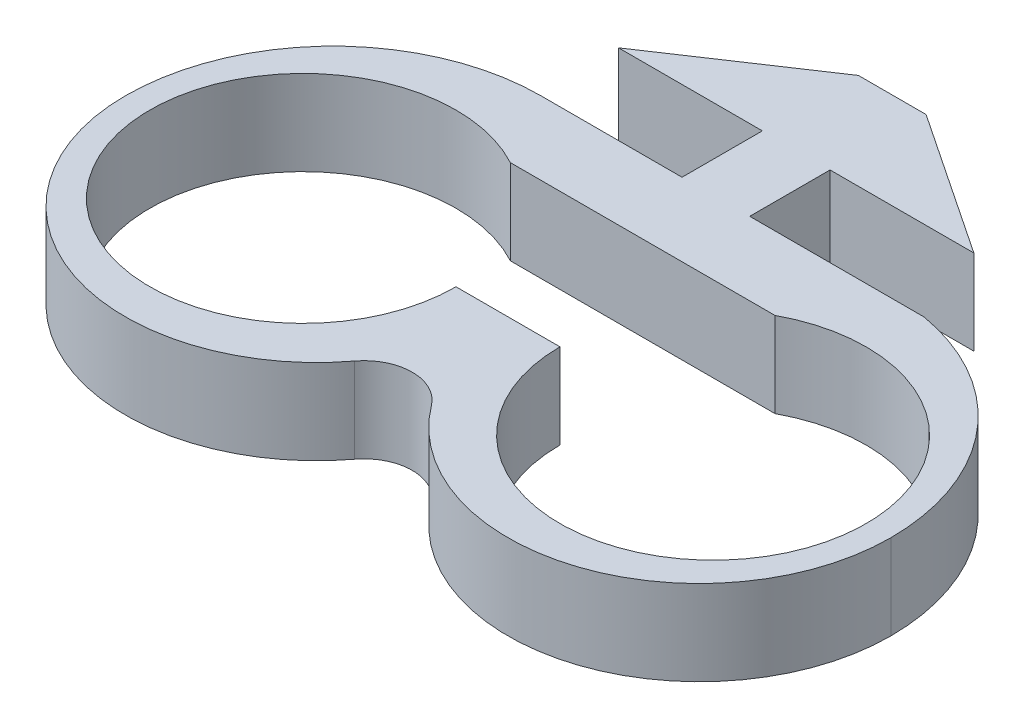
SolidWorks part; units mm, degrees
ref_plane "Front" through (0, 0, 0) normal (0, 0, 1) x (1, 0, 0)
ref_plane "Top" through (0, 0, 0) normal (0, 1, 0) x (1, 0, 0)
ref_plane "Right" through (0, 0, 0) normal (1, 0, 0) x (0, 0, -1)
sketch "Sketch1" plane through (0, 0, 0) normal (0, 1, 0) x (1, 0, 0)
  line L0 (-1.7907, 2.125) -> (-9.398, 2.125)
  line L2 (-1.7907, -2.125) -> (-1.7907, 2.125)
  line L4 (1.7907, -2.125) -> (1.7907, 2.125)
  line L7 (-9.398, 2.125) -> (-1.7907, 7.205)
  line L8 (-1.7907, 7.205) -> (1.7907, 7.205)
  line L9 (1.7907, 7.205) -> (9.398, 2.125)
  line L10 (9.398, 2.125) -> (1.7907, 2.125)
  line L11 (1.7907, -2.125) -> (20.25, -2.125)
  line L12 (-1.7907, -2.125) -> (-20.25, -2.125)
  line L13 (-20.25, -2.125) -> (-20.25, -13.1232)
  line L14 (-20.25, -13.1232) -> (20.25, -13.1232)
  line L15 (20.25, -13.1232) -> (20.25, -2.125)
  line L16 (20.25, -2.125) -> (1.7907, -2.125)
  point P0 (0, 0)
  point P17 (0, 7.205)
  point P19 (0, -13.1232)
  point P24 (1.7907, 0)
  dimension "D1" = 18.796
  dimension "D2" = 3.5814
  dimension "D3" = 40.5
  dimension "D4" = 10.9982
  dimension "D5" = 5.08
  dimension "4.2" = 4.25
extrude "Boss-Extrude1" add sketch "Sketch1" along normal blind 4.5 contours L14 L15 L11 L4 L10 L9 L8 L7 L0 L2 L12 L13
sketch "Sketch3" plane through (0, 4.5, 0) normal (0, 1, 0) x (1, 0, 0)
  line L3 (-20.25, -13.1232) -> (20.25, -13.1232) construction
  line L16 (-20.25, -13.1232) -> (20.25, -13.1232)
  line L17 (20.25, -13.1232) -> (20.25, -2.125)
  line L18 (20.25, -2.125) -> (1.7907, -2.125)
  line L19 (1.7907, -2.125) -> (1.7907, 2.125)
  line L20 (1.7907, 2.125) -> (9.398, 2.125)
  line L21 (9.398, 2.125) -> (1.7907, 7.205)
  line L22 (1.7907, 7.205) -> (-1.7907, 7.205)
  line L23 (-1.7907, 7.205) -> (-9.398, 2.125)
  line L24 (-9.398, 2.125) -> (-1.7907, 2.125)
  line L25 (-1.7907, 2.125) -> (-1.7907, -2.125)
  line L26 (-1.7907, -2.125) -> (-20.25, -2.125)
  line L27 (-20.25, -2.125) -> (-20.25, -13.1232)
  line L28 (-20.25, -13.1232) -> (20.25, -13.1232)
  arc A2 (-20.25, -13.1232) -> (-2.0306, -19.2057) centre (-10.125, -13.1232) ccw
  arc A3 (2.0306, -19.2057) -> (20.25, -13.1232) centre (10.125, -13.1232) ccw
  arc A4 (2.0306, -19.2057) -> (-2.0306, -19.2057) centre (0, -20.7315) ccw
  point P14 (0, -13.1232)
  line M15 (-20.25, -13.1232) -> (20.25, -13.1232)
  dimension "D2" = 2.54
  dimension "D1" = 0
extrude "Boss-Extrude2" add sketch "Sketch3" against normal up to surface (4.5 mm away) contours A2 M15 | L28 A3 up to face at (0, 0, 0.9864)
sketch "Sketch4" plane through (0, 4.5, 0) normal (0, 1, 0) x (1, 0, 0)
  line L1 (2.75, -13.1232) -> (-2.75, -13.1232) construction
  circle A0 centre (-10.85, -13.1232) radius 8.1
  circle A1 centre (10.85, -13.1232) radius 8.1
  point P4 (0, -13.1232)
  dimension "D1" = 16.2
  dimension "D2" = 21.7
extrude "Cut-Extrude2" cut sketch "Sketch4" against normal through all
sketch "Sketch5" plane through (0, 4.5, 0) normal (0, 1, 0) x (1, 0, 0)
  line L2 (7, -5.9967) -> (-7, -5.9967)
  line L10 (-2.75, -13.1232) -> (2.75, -13.1232)
  circle A0 centre (-10.85, -13.1232) radius 8.1 construction
  circle A1 centre (10.85, -13.1232) radius 8.1 construction
  arc A8 (7, -5.9967) -> (2.75, -13.1232) centre (10.85, -13.1232) ccw
  arc A9 (-2.75, -13.1232) -> (-7, -5.9967) centre (-10.85, -13.1232) ccw
  point P12 (0, -15.6632)
  point P28 (0, -10.5832)
  dimension "D2" = 14
  dimension "D3" = 2.54
  dimension "D10" = 2.54
extrude "Cut-Extrude4" cut sketch "Sketch5" against normal up to next contours A9 L2 A8 L10
sketch "Sketch6" plane through (0, 4.5, 0) normal (0, 1, 0) x (1, 0, 0)
  line L0 (-9.2518, -2.125) -> (-20.25, -2.125)
  line L1 (-20.25, -2.125) -> (-20.25, -13.1232)
  line L2 (-1.7907, -2.125) -> (-20.25, -2.125) construction
  line L3 (20.25, -13.1232) -> (20.25, -2.125)
  line L4 (20.25, -2.125) -> (11.0204, -2.125)
  line L5 (1.7907, -2.125) -> (20.25, -2.125) construction
  arc A0 (-9.2518, -2.125) -> (-20.25, -13.1232) centre (-9.2518, -13.1232) ccw
  arc A2 (20.25, -13.1232) -> (11.0204, -2.125) centre (9.0824, -13.1232) ccw
extrude "Cut-Extrude5" cut sketch "Sketch6" against normal up to next
